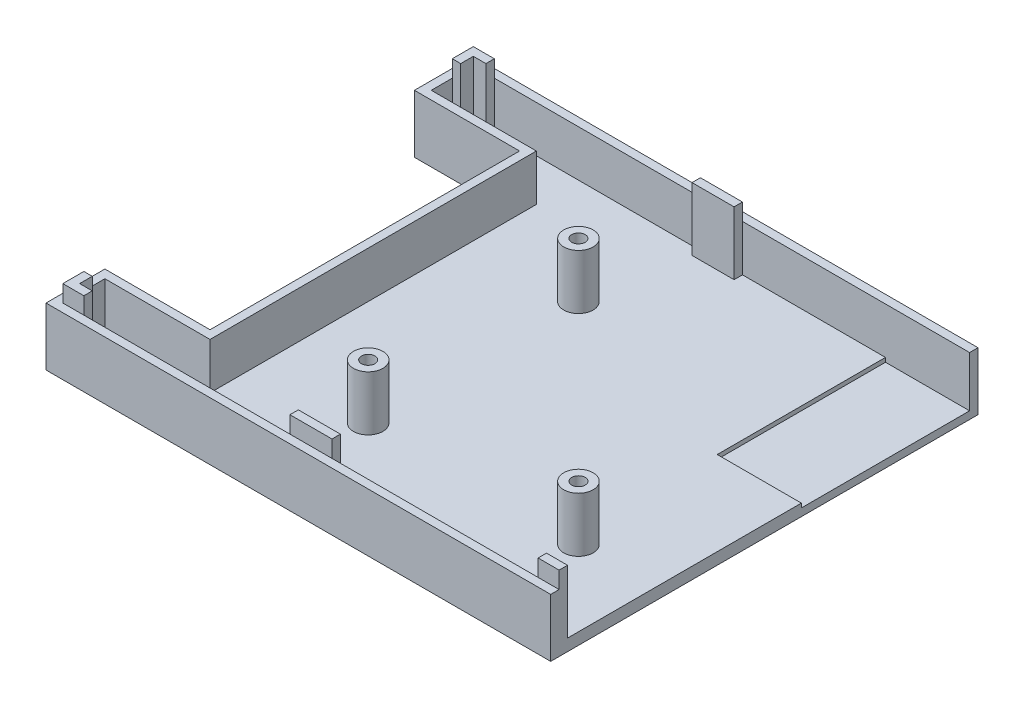
SolidWorks part; units mm, degrees
ref_plane "前视基准面" through (0, 0, 0) normal (0, 0, 1) x (1, 0, 0)
ref_plane "上视基准面" through (0, 0, 0) normal (0, 1, 0) x (1, 0, 0)
ref_plane "右视基准面" through (0, 0, 0) normal (1, 0, 0) x (0, 0, -1)
other "Configuration Table"
sketch "草图1" plane through (0, 0, 0) normal (0, 1, 0) x (1, 0, 0)
  line L1 (0, 0) -> (120, 0)
  line L2 (0, 0) -> (0, -101.6)
  line L3 (0, -101.6) -> (120, -101.6)
  line L4 (120, 0) -> (120, -101.6)
  dimension "D1" = 120
  dimension "D2" = 101.6
extrude "凸台-拉伸1" add sketch "草图1" along normal blind 13.8
sketch "草图2" plane through (0, 13.8, 0) normal (0, 1, 0) x (1, 0, 0)
  line L0 (0, 0) -> (0, -101.6) construction
  line L1 (0, -14) -> (25, -14)
  line L2 (0, -14) -> (0, -87.6)
  line L3 (0, -87.6) -> (25, -87.6)
  line L4 (25, -14) -> (25, -87.6)
  line L5 (120, 0) -> (0, 0) construction
  dimension "D1" = 25
  dimension "D2" = 73.6
  dimension "D3" = 14
extrude "切除-拉伸1" cut sketch "草图2" against normal up to next
sketch "草图4" plane through (0, 13.8, 0) normal (0, 1, 0) x (1, 0, 0)
  line L0 (25, -87.6) -> (25, -14) construction
  line L1 (27, -2) -> (120, -2)
  line L2 (27, -2) -> (27, -99.6)
  line L3 (27, -99.6) -> (120, -99.6)
  line L4 (120, -2) -> (120, -99.6)
  line L5 (120, 0) -> (0, 0) construction
  line L6 (120, -101.6) -> (120, 0) construction
  line L7 (0, -101.6) -> (120, -101.6) construction
  dimension "D1" = 2
  dimension "D2" = 2
  dimension "D3" = 0
  dimension "D4" = 2
extrude "切除-拉伸2" cut sketch "草图4" against normal blind 11
sketch "草图5" plane through (0, 2.8, 0) normal (0, 1, 0) x (1, 0, 0)
  line L0 (120, -50.8) -> (3.5175, -50.8) construction
  line L1 (120, -99.6) -> (120, -2) construction
ref_plane "基准面1" through (0, 0, 50.8) normal (0, 0, -1) x (-1, 0, 0)
sketch "草图6" plane through (0, 13.8, 0) normal (0, 1, 0) x (1, 0, 0)
  line L0 (0, -87.6) -> (25, -87.6) construction
  line L1 (27, -99.6) -> (2, -99.6)
  line L2 (27, -99.6) -> (27, -89.6)
  line L3 (27, -89.6) -> (2, -89.6)
  line L4 (2, -99.6) -> (2, -89.6)
  line L5 (0, -87.6) -> (0, -101.6) construction
  dimension "D1" = 2
  dimension "D2" = 2
extrude "切除-拉伸3" cut sketch "草图6" against normal up to surface (11 mm away) up to face at (73.5, 2.8, 50.8)
mirror "镜向1" about plane through (0, 0, 50.8) normal (0, 0, -1) of "切除-拉伸3"
sketch "草图7" plane through (0, 2.8, 0) normal (0, 1, 0) x (1, 0, 0)
  line L0 (2, -94.6) -> (4, -94.6)
  line L1 (2, -89.6) -> (2, -99.6) construction
  line L2 (4, -94.6) -> (4, -97.6)
  line L3 (4, -97.6) -> (7, -97.6)
  line L4 (7, -97.6) -> (7, -99.6)
  line L5 (2, -99.6) -> (120, -99.6) construction
  line L6 (7, -99.6) -> (2, -99.6)
  line L7 (2, -99.6) -> (2, -94.6)
  line L8 (2, -99.6) -> (120, -99.6) construction
  line L9 (120, -99.6) -> (115, -99.6)
  line L10 (120, -99.6) -> (120, -97.6)
  line L11 (120, -97.6) -> (115, -97.6)
  line L12 (115, -99.6) -> (115, -97.6)
  line L13 (56, -99.6) -> (66, -99.6)
  line L14 (56, -99.6) -> (56, -97.6)
  line L15 (56, -97.6) -> (66, -97.6)
  line L16 (66, -99.6) -> (66, -97.6)
  point P20 (61, -97.6)
  point P23 (61, -99.6)
  dimension "D1" = 2
  dimension "D2" = 2
  dimension "D3" = 5
  dimension "D4" = 5
  dimension "D5" = 2
  dimension "D6" = 10
  dimension "D7" = 0
  dimension "D8" = 2
extrude "凸台-拉伸2" add sketch "草图7" along normal blind 15
mirror "镜向2" about plane through (0, 0, 50.8) normal (0, 0, -1) of "凸台-拉伸2"
sketch "草图14" plane through (0, 17.8, 0) normal (0, 1, 0) x (1, 0, 0)
  line L6 (120, -2) -> (100, -2)
  line L7 (120, -2) -> (120, -42)
  line L8 (120, -42) -> (100, -42)
  line L9 (100, -2) -> (100, -42)
  dimension "D1" = 40
  dimension "D2" = 20
extrude "切除-拉伸9" cut sketch "草图14" against normal blind 16
sketch "草图15" plane through (0, 2.8, 0) normal (0, 1, 0) x (1, 0, 0)
  line L0 (56, -2) -> (7, -2) construction
  line L1 (0, 0) -> (0, -14) construction
  circle A0 centre (52, -27) radius 3.5
  circle A2 centre (52, -77) radius 3.5
  circle A3 centre (102, -77) radius 3.5
  dimension "D1" = 7
  dimension "D2" = 25
  dimension "D3" = 52
  dimension "D4" = 2
  dimension "D5" = 50
extrude "凸台-拉伸3" add sketch "草图15" along normal blind 13
sketch "草图16" plane through (0, 15.8, 0) normal (0, 1, 0) x (1, 0, 0)
  circle A0 centre (52, -27) radius 1.6
  circle A1 centre (52, -77) radius 1.6
  circle A2 centre (102, -77) radius 1.6
  dimension "D1" = 3.2
  dimension "D2" = 3.2
  dimension "D3" = 3.2
extrude "切除-拉伸10" cut sketch "草图16" against normal up to next
sketch "草图17" plane through (0, 0, 0) normal (0, -1, 0) x (1, 0, 0)
  circle A0 centre (52, 77) radius 2.65
  circle A1 centre (52, 27) radius 2.65
  circle A2 centre (102, 77) radius 2.65
  circle A3 centre (52, 27) radius 1.6 construction
  dimension "D1" = 5.3
  dimension "D3" = 0
  dimension "D2" = 2
extrude "切除-拉伸11" cut sketch "草图17" against normal blind 8
chamfer "倒角1" distance 2 angle 45 3 edges at (102, 0, 74.35) (52, 0, 74.35) (52, 0, 29.65)
